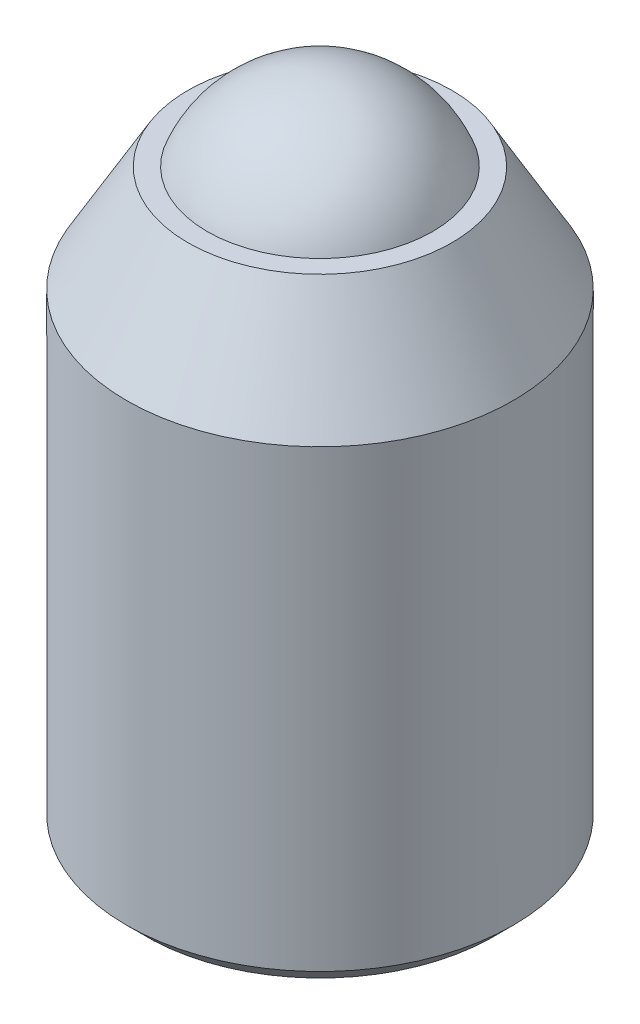
SolidWorks part; units mm, degrees
ref_plane "Front" through (0, 0, 0) normal (0, 0, 1) x (1, 0, 0)
ref_plane "Top" through (0, 0, 0) normal (0, 1, 0) x (1, 0, 0)
ref_plane "Right" through (0, 0, 0) normal (1, 0, 0) x (0, 0, -1)
sketch "Эскиз1" plane through (0, 0, 0) normal (0, 0, 1) x (1, 0, 0)
  line L2 (0, 0) -> (-2, 0)
  line L5 (0, 6.8) -> (0, 0)
  line L6 (-1.3662, 6) -> (-1.1662, 6)
  line L7 (-2, 0) -> (-2, 4.9022)
  line L8 (-2, 4.9022) -> (-1.3662, 6)
  arc A0 (0, 6.8) -> (-1.1662, 6) centre (0, 5.55) ccw
  dimension "D3" = 2.5
  dimension "D1" = 2
  dimension "D2" = 6
  dimension "D4" = 150
  dimension "D5" = 0.2
  dimension "D6" = 0.8
revolve "Повернуть1" add sketch "Эскиз1" angle 360 about L5
chamfer "Фаска1" distance 0.2 angle 45 1 edges at (0, 0, 2)
sketch "Эскиз2" plane through (0, 0, 0) normal (0, -1, 0) x (1, 0, 0)
  line L1 (1.1547, 0) -> (0.5774, 1)
  line L2 (0.5774, 1) -> (-0.5774, 1)
  line L3 (-0.5774, 1) -> (-1.1547, 0)
  line L4 (-1.1547, 0) -> (-0.5774, -1)
  line L5 (-0.5774, -1) -> (0.5774, -1)
  line L6 (0.5774, -1) -> (1.1547, 0)
  circle A0 centre (0, 0) radius 1 construction
  dimension "D1" = 2
extrude "Вырез-Вытянуть1" cut sketch "Эскиз2" against normal blind 1.5
chamfer "Фаска3" distance 0.25 angle 45 6 edges at (-0.866, 0, -0.5) (0, 0, -1) (0.866, 0, -0.5) (0.866, 0, 0.5) (0, 0, 1) (-0.866, 0, 0.5)
